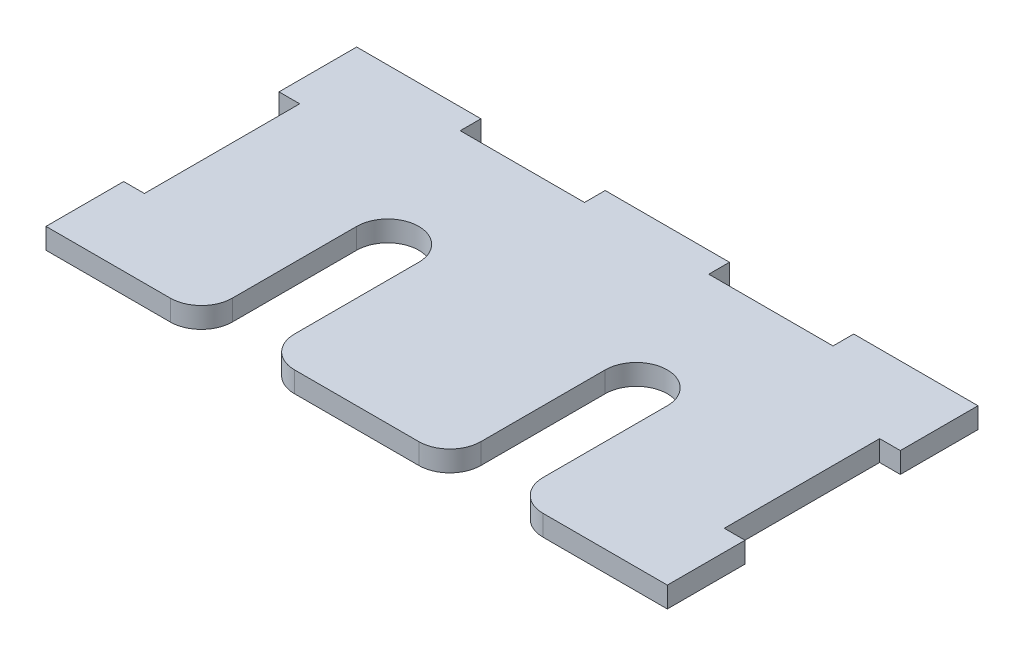
SolidWorks part; units mm, degrees
ref_plane "Front Plane" through (0, 0, 0) normal (0, 0, 1) x (1, 0, 0)
ref_plane "Top Plane" through (0, 0, 0) normal (0, 1, 0) x (1, 0, 0)
ref_plane "Right Plane" through (0, 0, 0) normal (1, 0, 0) x (0, 0, -1)
sketch "Sketch1" plane through (0, 0, 0) normal (0, 1, 0) x (1, 0, 0)
  line L1 (-45, -22.5) -> (45, -22.5)
  line L2 (-45, -22.5) -> (-45, 22.5)
  line L3 (-45, 22.5) -> (45, 22.5)
  line L4 (45, -22.5) -> (45, 22.5)
  line L5 (-45, -22.5) -> (45, 22.5) construction
  line L6 (-45, 22.5) -> (45, -22.5) construction
  point P0 (0, 0)
  dimension "D1" = 90
  dimension "D2" = 45
extrude "Boss-Extrude1" add sketch "Sketch1" along normal blind 3
sketch "Sketch2" plane through (0, 3, 0) normal (0, 1, 0) x (1, 0, 0)
  line L0 (-45, -22.5) -> (45, -22.5) construction
  line L1 (-22.5, -22.5) -> (-13.5, -22.5)
  line L2 (-22.5, -22.5) -> (-22.5, 0)
  line L4 (-13.5, -22.5) -> (-13.5, 0)
  line L5 (-45, 22.5) -> (-45, -22.5) construction
  line L6 (45, -22.5) -> (45, 22.5) construction
  line L7 (13.5, -22.5) -> (22.5, -22.5)
  line L8 (13.5, -22.5) -> (13.5, 0)
  line L10 (22.5, -22.5) -> (22.5, 0)
  arc A0 (-22.5, 0) -> (-13.5, 0) centre (-18, 0) cw
  arc A1 (13.5, 0) -> (22.5, 0) centre (18, 0) cw
  point P6 (-18, -22.5)
  point P13 (18, -22.5)
  dimension "D1" = 9
  dimension "D2" = 22.5
  dimension "D3" = 27
  dimension "D4" = 22.5
  dimension "D5" = 9
  dimension "D6" = 27
  dimension "D7" = 27
extrude "Cut-Extrude1" cut sketch "Sketch2" against normal blind 3
fillet "Fillet1" radius 4.5 4 edges at (-22.5, 1.5, 22.5) (-13.5, 1.5, 22.5) (13.5, 1.5, 22.5) (22.5, 1.5, 22.5)
sketch "Sketch4" plane through (0, 3, 0) normal (0, 1, 0) x (1, 0, 0)
  line L0 (-45, 22.5) -> (-45, -22.5) construction
  line L1 (-45, 11.25) -> (-42, 11.25)
  line L2 (-45, 11.25) -> (-45, -11.25)
  line L3 (-45, -11.25) -> (-42, -11.25)
  line L4 (-42, 11.25) -> (-42, -11.25)
  line L5 (45, 22.5) -> (-45, 22.5) construction
  line L6 (-27, 22.5) -> (-9, 22.5)
  line L7 (-27, 22.5) -> (-27, 19.5)
  line L8 (-27, 19.5) -> (-9, 19.5)
  line L9 (-9, 22.5) -> (-9, 19.5)
  line L10 (45, -22.5) -> (45, 22.5) construction
  line L11 (9, 22.5) -> (27, 22.5)
  line L12 (9, 22.5) -> (9, 19.5)
  line L13 (9, 19.5) -> (27, 19.5)
  line L14 (27, 22.5) -> (27, 19.5)
  line L15 (45, 11.25) -> (42, 11.25)
  line L16 (45, 11.25) -> (45, -11.25)
  line L17 (45, -11.25) -> (42, -11.25)
  line L18 (42, 11.25) -> (42, -11.25)
  point P22 (-45, 0)
  point P24 (45, 0)
  point P27 (-18, 22.5)
  point P28 (18, 22.5)
  dimension "D1" = 3
  dimension "D2" = 3
  dimension "D3" = 3
  dimension "D4" = 3
  dimension "D5" = 22.5
  dimension "D6" = 22.5
  dimension "D7" = 18
  dimension "D8" = 18
  dimension "D9" = 22.5
  dimension "D10" = 22.5
  dimension "D11" = 27
  dimension "D12" = 27
extrude "Cut-Extrude4" cut sketch "Sketch4" against normal blind 3
